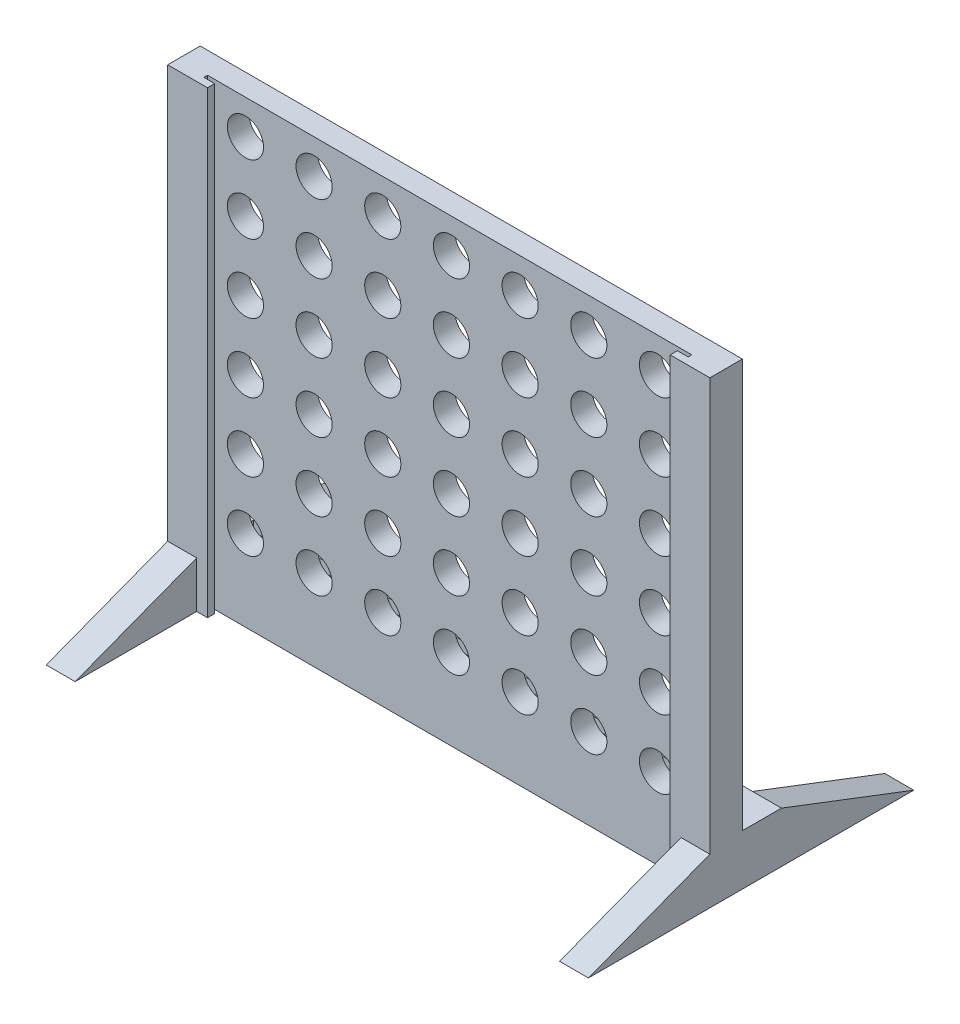
SolidWorks part; units mm, degrees
ref_plane "Front Plane" through (0, 0, 0) normal (0, 0, 1) x (1, 0, 0)
ref_plane "Top Plane" through (0, 0, 0) normal (0, 1, 0) x (1, 0, 0)
ref_plane "Right Plane" through (0, 0, 0) normal (1, 0, 0) x (0, 0, -1)
sketch "Sketch1" plane through (0, 0, 0) normal (0, 0, 1) x (1, 0, 0)
  line L1 (33.5, -28.25) -> (-33.5, -28.25)
  line L2 (33.5, -28.25) -> (33.5, 28.25)
  line L3 (33.5, 28.25) -> (-33.5, 28.25)
  line L4 (-33.5, -28.25) -> (-33.5, 28.25)
  line L5 (33.5, -28.25) -> (-33.5, 28.25) construction
  line L6 (33.5, 28.25) -> (-33.5, -28.25) construction
  circle A0 centre (-28.25, 23.5) radius 2.5
  circle A1 centre (-18.75, 23.5) radius 2.5
  circle A2 centre (-9.25, 23.5) radius 2.5
  circle A3 centre (0.25, 23.5) radius 2.5
  circle A4 centre (9.75, 23.5) radius 2.5
  circle A5 centre (19.25, 23.5) radius 2.5
  circle A6 centre (28.75, 23.5) radius 2.5
  circle A7 centre (-18.75, 14) radius 2.5
  circle A8 centre (-9.25, 14) radius 2.5
  circle A9 centre (0.25, 14) radius 2.5
  circle A10 centre (9.75, 14) radius 2.5
  circle A11 centre (19.25, 14) radius 2.5
  circle A12 centre (28.75, 14) radius 2.5
  circle A13 centre (-18.75, 4.5) radius 2.5
  circle A14 centre (-9.25, 4.5) radius 2.5
  circle A15 centre (0.25, 4.5) radius 2.5
  circle A16 centre (9.75, 4.5) radius 2.5
  circle A17 centre (19.25, 4.5) radius 2.5
  circle A18 centre (28.75, 4.5) radius 2.5
  circle A19 centre (-18.75, -5) radius 2.5
  circle A20 centre (-9.25, -5) radius 2.5
  circle A21 centre (0.25, -5) radius 2.5
  circle A22 centre (9.75, -5) radius 2.5
  circle A23 centre (19.25, -5) radius 2.5
  circle A24 centre (28.75, -5) radius 2.5
  circle A25 centre (-18.75, -14.5) radius 2.5
  circle A26 centre (-9.25, -14.5) radius 2.5
  circle A27 centre (0.25, -14.5) radius 2.5
  circle A28 centre (9.75, -14.5) radius 2.5
  circle A29 centre (19.25, -14.5) radius 2.5
  circle A30 centre (28.75, -14.5) radius 2.5
  circle A31 centre (-18.75, -24) radius 2.5
  circle A32 centre (-9.25, -24) radius 2.5
  circle A33 centre (0.25, -24) radius 2.5
  circle A34 centre (9.75, -24) radius 2.5
  circle A35 centre (19.25, -24) radius 2.5
  circle A36 centre (28.75, -24) radius 2.5
  circle A37 centre (-28.25, 14) radius 2.5
  circle A38 centre (-28.25, 4.5) radius 2.5
  circle A39 centre (-28.25, -5) radius 2.5
  circle A40 centre (-28.25, -14.5) radius 2.5
  circle A41 centre (-28.25, -24) radius 2.5
  point P0 (0, 0)
  dimension "D3" = 5
  dimension "D1" = 67
  dimension "D2" = 56.5
  dimension "D4" = 5.25
  dimension "D5" = 4.75
  dimension "D6" = 7
  dimension "D7" = 6
extrude "Boss-Extrude1" add sketch "Sketch1" along normal blind 3
sketch "Sketch2" plane through (33.5, 0, 0) normal (1, 0, 0) x (0, 0, -1)
  line L0 (0, -28.25) -> (0, 28.25) construction
  line L1 (-3, -28.25) -> (5.4, -28.25)
  line L2 (-3, -28.25) -> (-3, -35.25)
  line L3 (-3, -35.25) -> (5.4, -35.25)
  line L4 (5.4, -28.25) -> (5.4, -35.25)
  line L5 (3.4, -28.25) -> (2, -28.25)
  line L6 (3.4, -28.25) -> (3.4, -33.25)
  line L7 (3.4, -33.25) -> (2, -33.25)
  line L8 (2, -28.25) -> (2, -33.25)
  line M11 (-3, -28.25) -> (0, -28.25)
  dimension "D1" = 1.4
  dimension "D2" = 2
  dimension "D3" = 2
  dimension "D4" = 5
  dimension "D5" = 2
extrude "Boss-Extrude2" add sketch "Sketch2" against normal up to surface (67 mm away) contours L8 L1 L2 L3 L4 L6 L7 M11 up to face at (-33.5, 0, 1.5)
sketch "Sketch3" plane through (-33.5, 0, 0) normal (-1, 0, 0) x (0, 0, 1)
  line L0 (-5.4, -28.25) -> (-23.7, -35.25)
  line L1 (-23.7, -35.25) -> (21.3, -35.25)
  line L2 (21.3, -35.25) -> (3, -28.25)
  line L3 (3, 28.25) -> (3, -35.25) construction
  line L4 (3, -28.25) -> (-5.4, -28.25)
  line L5 (-2, -28.25) -> (0, -28.25) construction
  line L6 (-5.4, -35.25) -> (3, -35.25) construction
  point P9 (-1.2, -35.25)
  point P12 (-1.2, -35.25)
  dimension "D1" = 45
extrude "Boss-Extrude3" add sketch "Sketch3" along normal blind 4
sketch "Sketch4" plane through (33.5, 0, 0) normal (1, 0, 0) x (0, 0, -1)
  line L0 (5.4, -28.25) -> (23.7, -35.25)
  line L1 (23.7, -35.25) -> (-21.3, -35.25)
  line L2 (-21.3, -35.25) -> (-3, -28.25)
  line L3 (-3, -35.25) -> (-3, 28.25) construction
  line L4 (-3, -28.25) -> (5.4, -28.25)
  line L5 (0, -28.25) -> (2, -28.25) construction
  line L6 (-3, -35.25) -> (5.4, -35.25) construction
  point P9 (1.2, -35.25)
  point P12 (1.2, -35.25)
  dimension "D1" = 45
extrude "Boss-Extrude4" add sketch "Sketch4" along normal blind 4
sketch "Sketch6" plane through (0, -35.25, 0) normal (0, -1, 0) x (1, 0, 0)
  line L0 (33.5, 21.3) -> (33.5, 3) construction
  line L1 (33.5, 3.5) -> (32, 3.5)
  line L2 (33.5, 3.5) -> (33.5, 4.5)
  line L3 (33.5, 4.5) -> (32, 4.5)
  line L4 (32, 3.5) -> (32, 4.5)
  line L5 (-33.5, 3) -> (-33.5, 21.3) construction
  line L6 (-33.5, 3.5) -> (-32, 3.5)
  line L7 (-33.5, 3.5) -> (-33.5, 4.5)
  line L8 (-33.5, 4.5) -> (-32, 4.5)
  line L9 (-32, 3.5) -> (-32, 4.5)
  line L10 (-33.5, 3) -> (33.5, 3) construction
  line L11 (37.5, 21.3) -> (37.5, -23.7) construction
  line L12 (33.5, 4.5) -> (37.5, 4.5)
  line L13 (33.5, 4.5) -> (33.5, 0)
  line L14 (33.5, 0) -> (37.5, 0)
  line L15 (37.5, 4.5) -> (37.5, 0)
  line L16 (-37.5, -23.7) -> (-37.5, 21.3) construction
  line L17 (-33.5, 4.5) -> (-37.5, 4.5)
  line L18 (-33.5, 4.5) -> (-33.5, 0)
  line L19 (-33.5, 0) -> (-37.5, 0)
  line L20 (-37.5, 4.5) -> (-37.5, 0)
  line M15 (-33.5, 3) -> (-33.5, 21.3)
  line M17 (-37.5, 21.3) -> (-37.5, -23.7)
  line M23 (37.5, -23.7) -> (37.5, 21.3)
  line M25 (33.5, 21.3) -> (33.5, 3)
  dimension "D1" = 0.5
  dimension "D2" = 1
  dimension "D3" = 1.5
  dimension "D4" = 4.5
  dimension "D5" = 4.5
extrude "Boss-Extrude5" add sketch "Sketch6" against normal up to surface (63.5 mm away) contours L19 L18 L17 M15 M17 | L6 L9 L8 M15 | L13 L14 L12 M23 M25 | L4 L1 L3 M25 up to face at (0, 28.25, 1.5)
